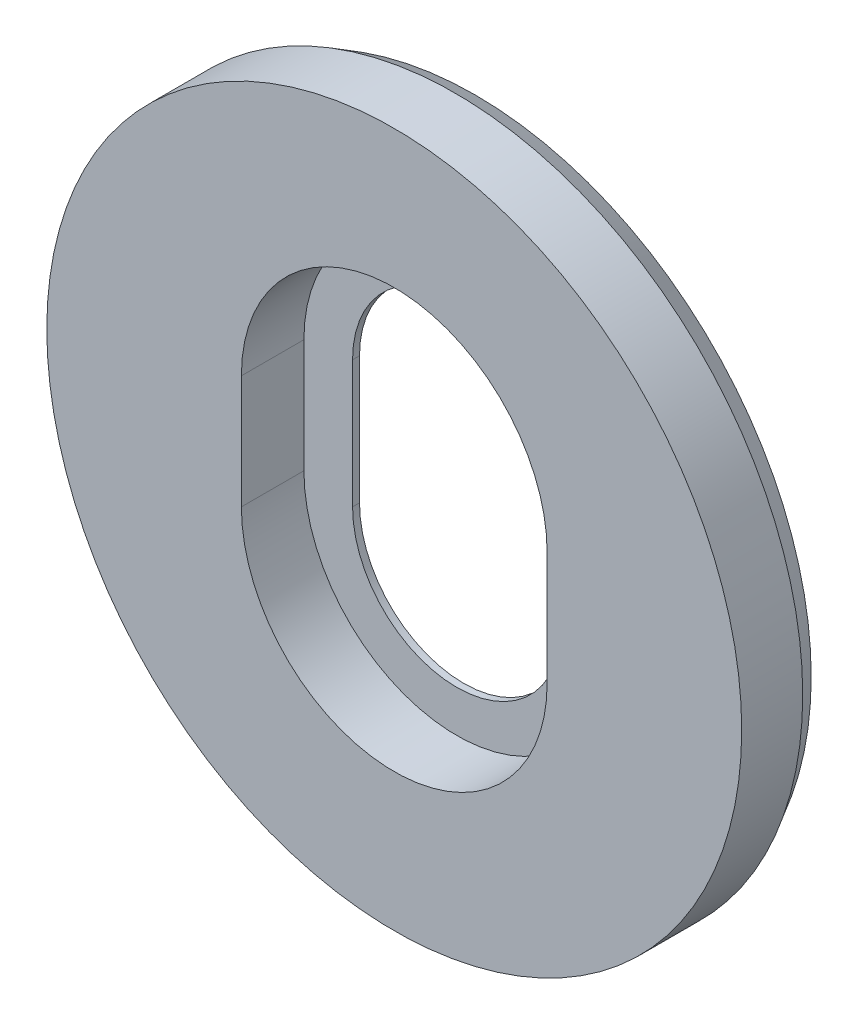
SolidWorks part; units mm, degrees
material "ABS"
ref_plane "Спереди" through (0, 0, 0) normal (0, 0, 1) x (1, 0, 0)
ref_plane "Сверху" through (0, 0, 0) normal (0, 1, 0) x (1, 0, 0)
ref_plane "Справа" through (0, 0, 0) normal (1, 0, 0) x (0, 0, -1)
sketch "Основание Э" plane through (0, 0, 0) normal (0, 0, 1) x (1, 0, 0)
  line L4 (0, 2.75) -> (0, -2.75) construction
  line L5 (4.5, 2.75) -> (4.5, -2.75)
  line L6 (-4.5, 2.75) -> (-4.5, -2.75)
  circle A0 centre (0, 0) radius 15
  arc A3 (4.5, 2.75) -> (-4.5, 2.75) centre (0, 2.75) ccw
  arc A4 (-4.5, -2.75) -> (4.5, -2.75) centre (0, -2.75) ccw
  point P2 (0, 0)
  point P3 (0, 0)
  point P4 (0, 0)
  point P7 (0, 0)
  point P38 (0, 7.25)
  point P39 (0, -7.25)
  point P41 (0, 0)
  dimension "D2" = 30
  dimension "D5" = 9
  dimension "D6" = 14.5
extrude "Основание" add sketch "Основание Э" along normal blind 3.5
sketch "Эскиз1" plane through (0, 0, 3.5) normal (0, 0, 1) x (1, 0, 0)
  line L4 (0, 2.45) -> (0, -2.45) construction
  line L5 (6.6, 2.45) -> (6.6, -2.45)
  line L6 (-6.6, 2.45) -> (-6.6, -2.45)
  line L7 (0, 2.75) -> (0, -2.75) construction
  arc A2 (6.6, 2.45) -> (-6.6, 2.45) centre (0, 2.45) ccw
  arc A3 (-6.6, -2.45) -> (6.6, -2.45) centre (0, -2.45) ccw
  point P13 (0, 0)
  point P22 (0, 9.05)
  point P23 (0, -9.05)
  dimension "D3" = 13.2
  dimension "D4" = 18.1
extrude "Динамики" cut sketch "Эскиз1" against normal offset from surface (2.7 mm away) 0.8 up to face at (15, 0, 0)
chamfer "Фаска1" distance 0.5 angle 60 5 edges at (4.5, 0, 0) (0, -7.25, 0) (-4.5, 0, 0) (0, 7.25, 0) (15, 0, 0)
